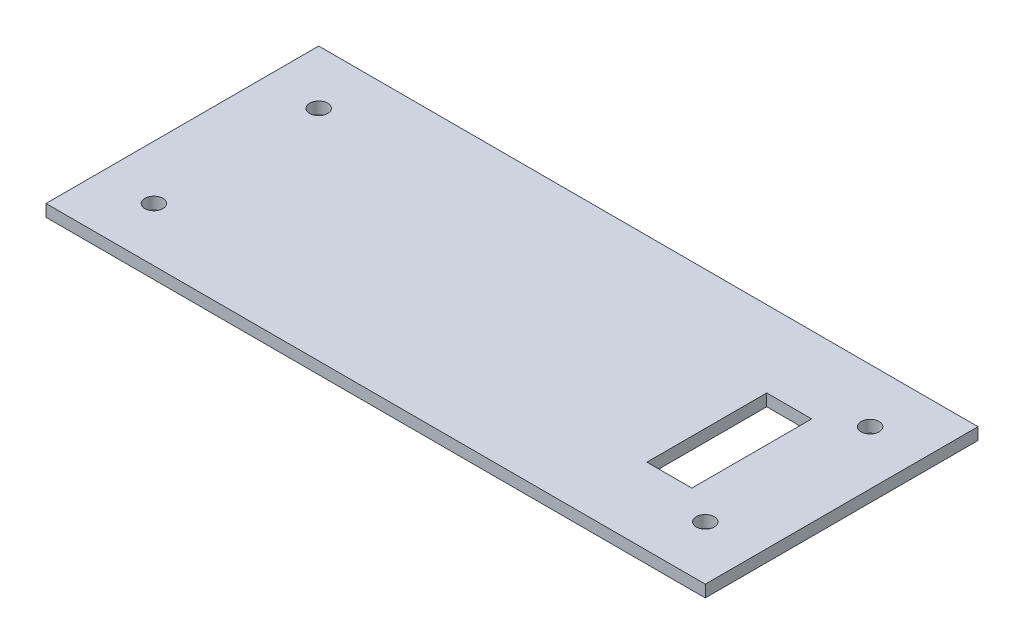
SolidWorks part; units mm, degrees
ref_plane "Front Plane" through (0, 0, 0) normal (0, 0, 1) x (1, 0, 0)
ref_plane "Top Plane" through (0, 0, 0) normal (0, 1, 0) x (1, 0, 0)
ref_plane "Right Plane" through (0, 0, 0) normal (1, 0, 0) x (0, 0, -1)
sketch "Sketch1" plane through (0, 0, 0) normal (0, 1, 0) x (1, 0, 0)
  line L1 (-55, 22.75) -> (55, 22.75)
  line L2 (-55, 22.75) -> (-55, -22.75)
  line L3 (-55, -22.75) -> (55, -22.75)
  line L4 (55, 22.75) -> (55, -22.75)
  line L5 (-55, 22.75) -> (55, -22.75) construction
  line L6 (-55, -22.75) -> (55, 22.75) construction
  point P0 (0, 0)
  dimension "D1" = 110
  dimension "D2" = 45.5
extrude "Boss-Extrude1" add sketch "Sketch1" along normal blind 2
sketch "Sketch2" plane through (0, 2, 0) normal (0, 1, 0) x (1, 0, 0)
  line L1 (-55, 22.75) -> (-55, -22.75) construction
  line L2 (-55, -22.75) -> (55, -22.75) construction
  line L3 (-55, 0) -> (55, 0) construction
  line L4 (55, -22.75) -> (55, 22.75) construction
  line L5 (0, -22.75) -> (0, 22.75) construction
  line L6 (55, 22.75) -> (-55, 22.75) construction
  line L8 (32.5, -10) -> (40, -10)
  line L9 (32.5, -10) -> (32.5, 10)
  line L10 (32.5, 10) -> (40, 10)
  line L11 (40, -10) -> (40, 10)
  line L12 (32.5, -10) -> (40, 10) construction
  line L13 (32.5, 10) -> (40, -10) construction
  circle A0 centre (-46, -13.75) radius 1.5
  circle A1 centre (-46, 13.75) radius 1.5
  circle A2 centre (46, 13.75) radius 1.5
  circle A3 centre (46, -13.75) radius 1.5
  point P20 (36.25, 0)
  dimension "D1" = 3
  dimension "D2" = 7.5
  dimension "D3" = 7.5
  dimension "D4" = 15
  dimension "D5" = 20
  dimension "D6" = 7.5
extrude "Cut-Extrude1" cut sketch "Sketch2" against normal up to next
